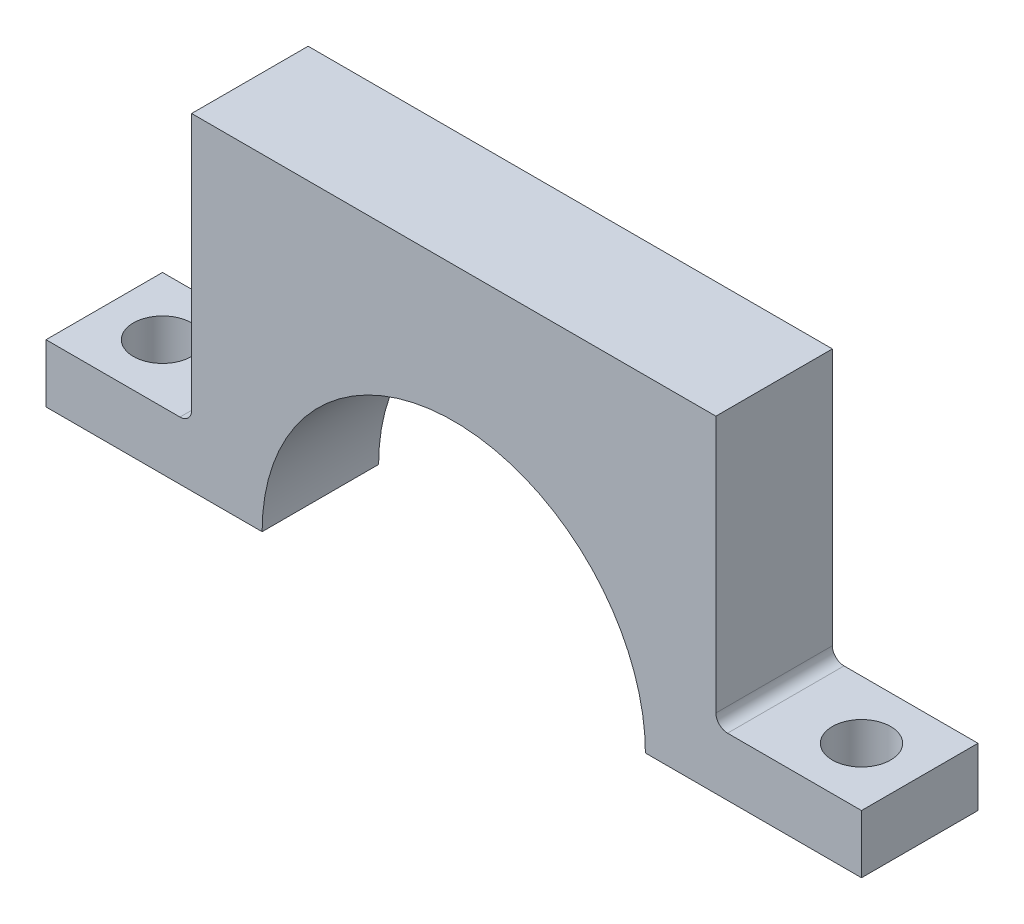
SolidWorks part; units mm, degrees
ref_plane "前视基准面" through (0, 0, 0) normal (0, 0, 1) x (1, 0, 0)
ref_plane "上视基准面" through (0, 0, 0) normal (0, 1, 0) x (1, 0, 0)
ref_plane "右视基准面" through (0, 0, 0) normal (1, 0, 0) x (0, 0, -1)
sketch "草图1" plane through (0, 0, 0) normal (0, 0, 1) x (1, 0, 0)
  line L0 (16.45, 0) -> (22.5, 0)
  line L1 (22.5, 0) -> (22.5, 28.0667)
  line L2 (22.5, 28.0667) -> (-22.5, 28.0667)
  line L3 (0, 0) -> (0, -7.8735) construction
  line L4 (-16.45, 0) -> (-22.5, 0)
  line L5 (-22.5, 0) -> (-22.5, 28.0667)
  arc A0 (16.45, 0) -> (-16.45, 0) centre (0, 0) ccw
  point P11 (0, 28.0667)
  dimension "D1" = 32.9
  dimension "D2" = 45
extrude "凸台-拉伸1" add sketch "草图1" along normal mid plane 10
sketch "草图2" plane through (0, 0, 0) normal (0, -1, 0) x (1, 0, 0)
  line L0 (-22.5, 5) -> (-22.5, -5)
  line L1 (-35, 5) -> (-22.5, 5)
  line L2 (-35, 5) -> (-35, -5)
  line L3 (-35, -5) -> (-22.5, -5)
  line L4 (35, 5) -> (35, -5)
  line L5 (0, -5) -> (0, 5) construction
  line L6 (-35, 0) -> (-22.5, 0) construction
  line L7 (-22.5, 5) -> (-22.5, -5) construction
  line L8 (22.5, 5) -> (22.5, -5)
  line L9 (22.5, 5) -> (35, 5)
  line L10 (22.5, 0) -> (35, 0) construction
  line L11 (22.5, -5) -> (35, -5)
  circle A0 centre (-30, 0) radius 2.5
  circle A1 centre (30, 0) radius 2.5
  point P0 (0, 0)
  dimension "D4" = 5
  dimension "D2" = 70
  dimension "D3" = 30
extrude "凸台-拉伸2" add sketch "草图2" against normal blind 5
fillet "圆角1" radius 1 2 edges at (22.5, 5, 0) (-22.5, 5, 0)
